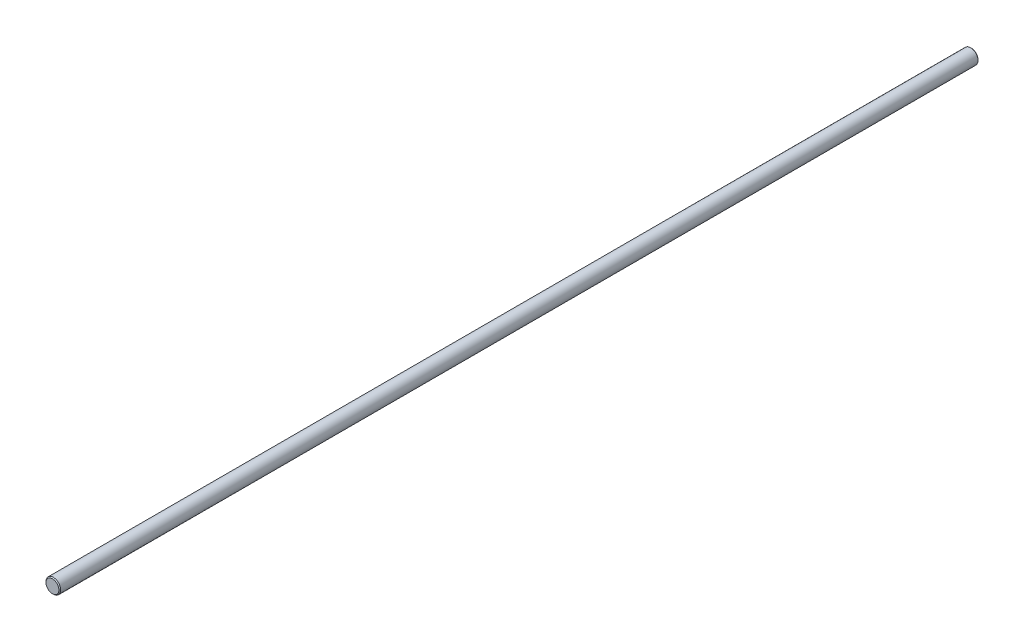
SolidWorks part; units mm, degrees
material "Chrome Stainless Steel"
ref_plane "Front Plane" through (0, 0, 0) normal (0, 0, 1) x (1, 0, 0)
ref_plane "Top Plane" through (0, 0, 0) normal (0, 1, 0) x (1, 0, 0)
ref_plane "Right Plane" through (0, 0, 0) normal (1, 0, 0) x (0, 0, -1)
sketch "Sketch1" plane through (0, 0, 0) normal (0, 0, 1) x (1, 0, 0)
  circle A0 centre (0, 0) radius 4
  dimension "D1" = 8
extrude "Boss-Extrude1" add sketch "Sketch1" along normal blind 500
chamfer "Chamfer1" distance 0.5 angle 44 2 edges at (4, 0, 0) (4, 0, 500)
